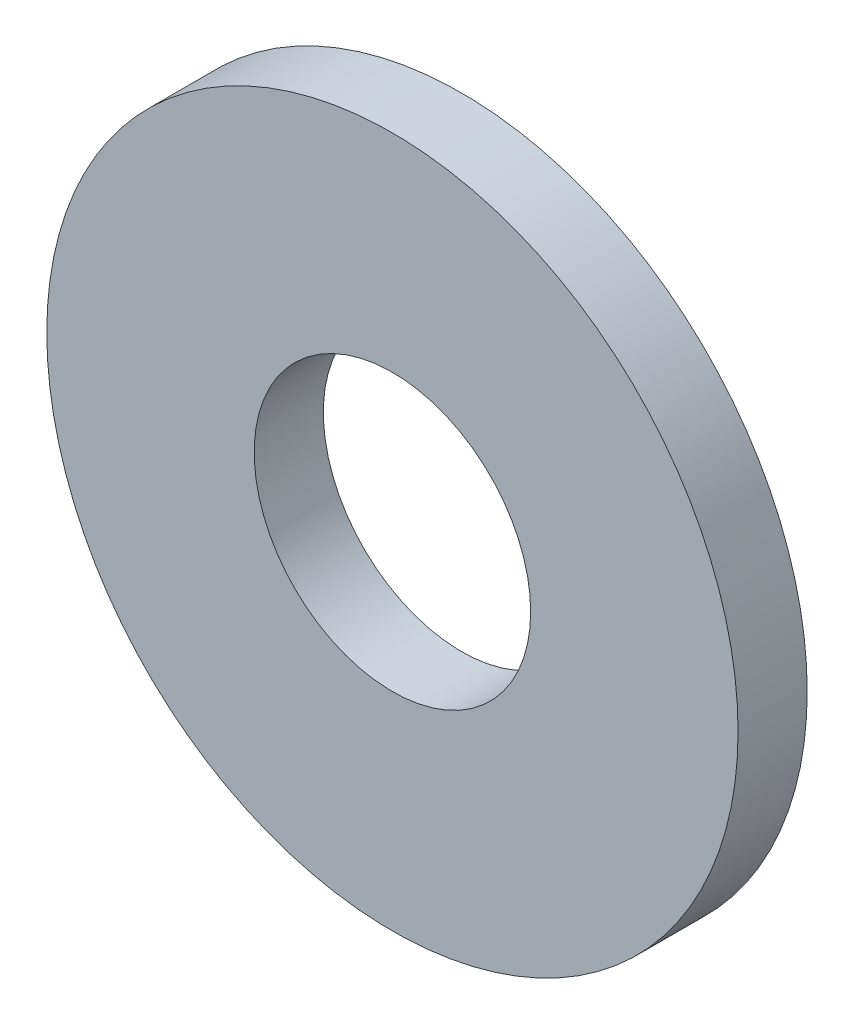
SolidWorks part; units mm, degrees
ref_plane "Front Plane" through (0, 0, 0) normal (0, 0, 1) x (1, 0, 0)
ref_plane "Top Plane" through (0, 0, 0) normal (0, 1, 0) x (1, 0, 0)
ref_plane "Right Plane" through (0, 0, 0) normal (1, 0, 0) x (0, 0, -1)
sketch "Sketch1" plane through (0, 0, 0) normal (0, 0, 1) x (1, 0, 0)
  circle A0 centre (0, 0) radius 1
  circle A1 centre (0, 0) radius 2.5
  dimension "D1" = 2
  dimension "D2" = 5
extrude "Boss-Extrude1" add sketch "Sketch1" along normal blind 0.5
